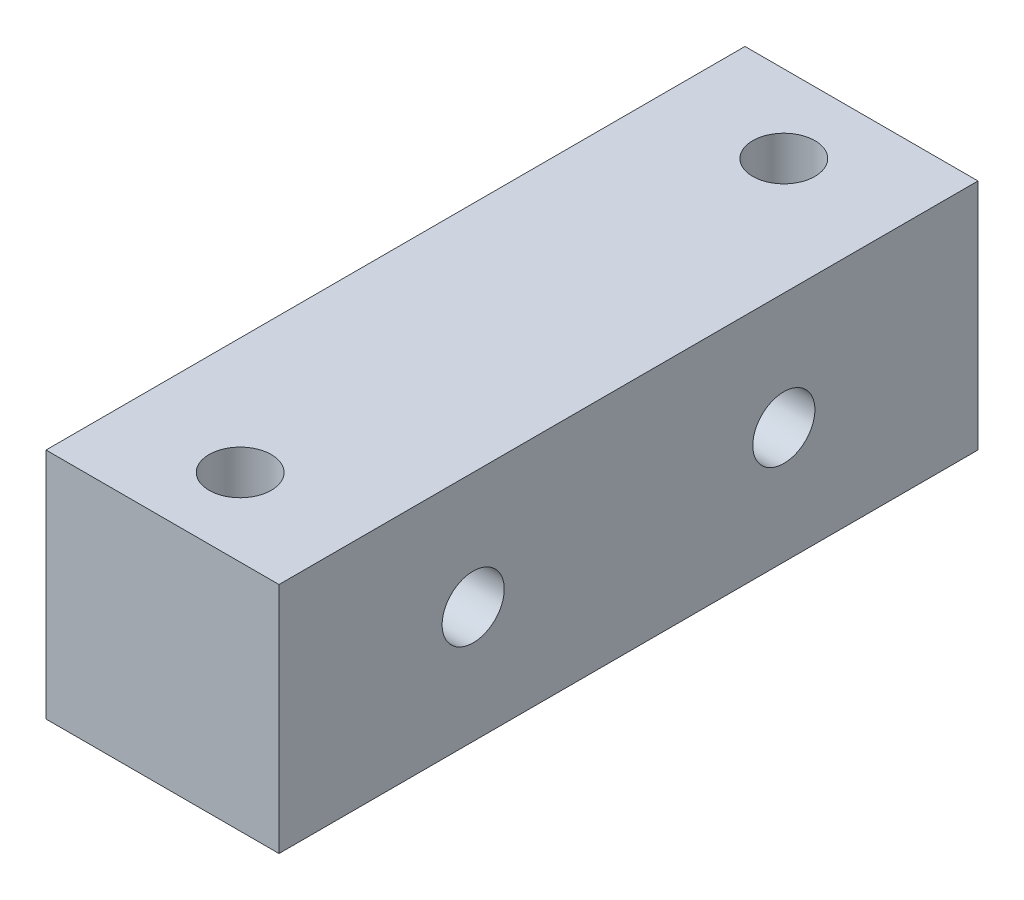
SolidWorks part; units mm, degrees
ref_plane "Front Plane" through (0, 0, 0) normal (0, 0, 1) x (1, 0, 0)
ref_plane "Top Plane" through (0, 0, 0) normal (0, 1, 0) x (1, 0, 0)
ref_plane "Right Plane" through (0, 0, 0) normal (1, 0, 0) x (0, 0, -1)
sketch "Sketch1" plane through (0, 0, 0) normal (0, 1, 0) x (1, 0, 0)
  line L1 (-15, -45) -> (15, -45)
  line L2 (-15, -45) -> (-15, 45)
  line L3 (-15, 45) -> (15, 45)
  line L4 (15, -45) -> (15, 45)
  line L5 (-15, -45) -> (15, 45) construction
  line L6 (-15, 45) -> (15, -45) construction
  point P0 (0, 0)
  dimension "D1" = 30
  dimension "D2" = 90
extrude "Boss-Extrude1" add sketch "Sketch1" along normal blind 30
sketch "Sketch2" plane through (-15, 0, 0) normal (-1, 0, 0) x (0, 0, 1)
  line L0 (0, 0) -> (0, 30) construction
  line L1 (-45, 0) -> (45, 0) construction
  line L2 (-45, 30) -> (45, 30) construction
  line L3 (-45, 15) -> (45, 15) construction
  line L4 (-45, 30) -> (-45, 0) construction
  line L5 (45, 30) -> (45, 0) construction
  circle A0 centre (-20, 15) radius 4
  circle A1 centre (20, 15) radius 4
  dimension "D1" = 8
  dimension "D2" = 40
extrude "Cut-Extrude1" cut sketch "Sketch2" against normal through all
sketch "Sketch3" plane through (0, 30, 0) normal (0, 1, 0) x (1, 0, 0)
  line L0 (0, 45) -> (0, -45) construction
  line L1 (15, 45) -> (-15, 45) construction
  line L2 (-15, -45) -> (15, -45) construction
  line L3 (-15, 0) -> (15, 0) construction
  line L4 (-15, 45) -> (-15, -45) construction
  line L5 (15, -45) -> (15, 45) construction
  circle A0 centre (0, 35) radius 4
  circle A1 centre (0, -35) radius 4
  dimension "D1" = 8
  dimension "D2" = 70
extrude "Cut-Extrude2" cut sketch "Sketch3" against normal through all
